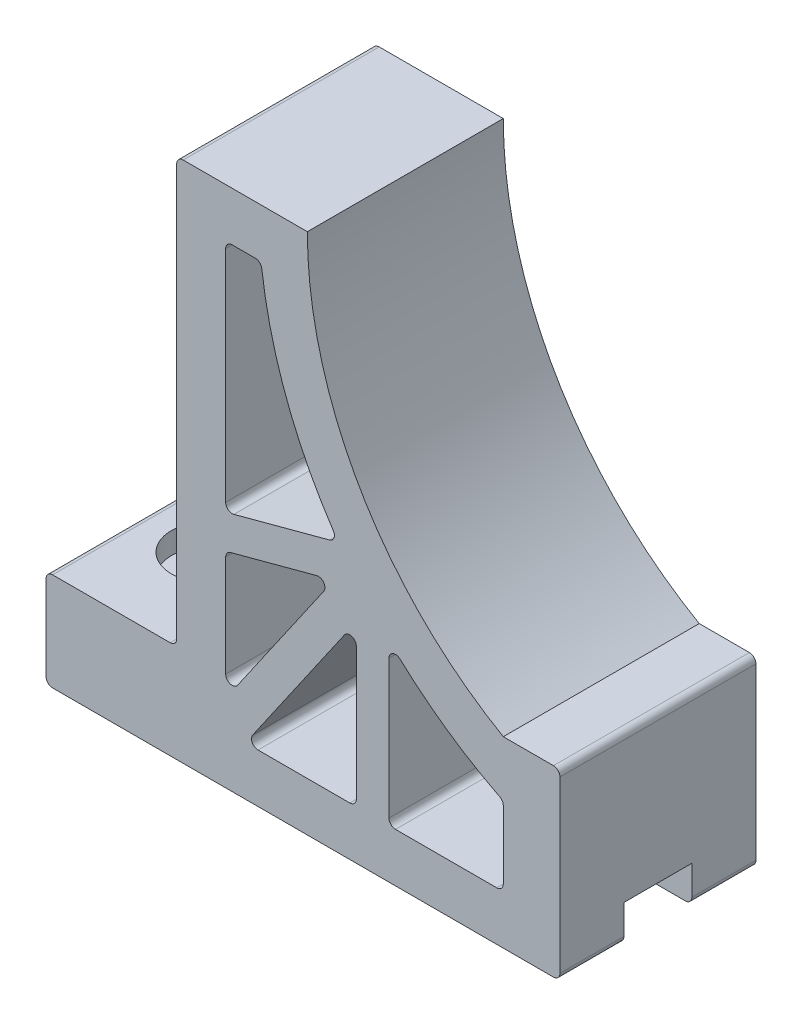
SolidWorks part; units mm, degrees
ref_plane "Front Plane" through (0, 0, 0) normal (0, 0, 1) x (1, 0, 0)
ref_plane "Top Plane" through (0, 0, 0) normal (0, 1, 0) x (1, 0, 0)
ref_plane "Right Plane" through (0, 0, 0) normal (1, 0, 0) x (0, 0, -1)
sketch "Sketch1" plane through (0, 0, 0) normal (0, 0, 1) x (1, 0, 0)
  line L1 (101.6, -50.8) -> (-101.6, -50.8)
  line L2 (101.6, -50.8) -> (101.6, 50.8)
  line L3 (101.6, 50.8) -> (-101.6, 50.8)
  line L4 (-101.6, -50.8) -> (-101.6, 50.8)
  line L5 (101.6, -50.8) -> (-101.6, 50.8) construction
  line L6 (101.6, 50.8) -> (-101.6, -50.8) construction
  point P0 (0, 0)
  dimension "D1" = 203.2
  dimension "4" = 101.6
extrude "Boss-Extrude1" add sketch "Sketch1" along normal blind 38.1
sketch "Sketch2" plane through (0, 0, 38.1) normal (0, 0, 1) x (1, 0, 0)
  line L0 (-101.6, -50.8) -> (101.6, -50.8) construction
  circle A0 centre (0, 50.8) radius 76.2
  dimension "D1" = 152.4
  dimension "D2" = 101.6
extrude "Cut-Extrude1" cut sketch "Sketch2" against normal through all
sketch "Sketch3" plane through (-101.6, 0, 0) normal (-1, 0, 0) x (0, 0, 1)
  line L0 (38.1, 50.8) -> (38.1, -50.8) construction
  line L1 (0, -50.8) -> (38.1, -50.8)
  line L2 (0, -50.8) -> (0, -31.75)
  line L3 (0, -31.75) -> (38.1, -31.75)
  line L4 (38.1, -50.8) -> (38.1, -31.75)
  dimension "D1" = 19.05
extrude "Boss-Extrude2" add sketch "Sketch3" along normal blind 25.4
sketch "Sketch4" plane through (0, 0, 38.1) normal (0, 0, 1) x (1, 0, 0)
  line L7 (-85.1942, 41.275) -> (-92.075, 41.275)
  line L8 (-92.075, 41.275) -> (-92.075, -41.275)
  line L9 (-92.075, -41.275) -> (-36.6025, -41.275)
  line L10 (-36.6025, -41.275) -> (-36.6025, -26.7179)
  line L11 (-101.6, 50.8) -> (-101.6, -31.75) construction
  line L12 (-76.2, 50.8) -> (-101.6, 50.8) construction
  line L13 (-127, -50.8) -> (101.6, -50.8) construction
  arc A4 (-36.6025, -26.7179) -> (-85.1942, 41.275) centre (0, 50.8) cw
  dimension "D1" = 85.725
  dimension "D2" = 9.525
  dimension "D3" = 9.525
  dimension "D4" = 9.525
extrude "Cut-Extrude2" cut sketch "Sketch4" against normal through all
sketch "Sketch5" plane through (0, 0, 38.1) normal (0, 0, 1) x (1, 0, 0)
  line L0 (-63.5, 0) -> (-97.8822, -9.2127) construction
  line L1 (-62.6782, -3.0668) -> (-97.0604, -12.2795)
  line L2 (-64.3218, 3.0668) -> (-98.7039, -6.1459)
  line L3 (0, 0) -> (-140.7402, 0) construction
  arc A0 (-62.6782, -3.0668) -> (-64.3218, 3.0668) centre (-63.5, 0) ccw
  arc A1 (-98.7039, -6.1459) -> (-97.0604, -12.2795) centre (-97.8822, -9.2127) ccw
  point P2 (-80.6911, -4.6063)
  dimension "D1" = 3.175
  dimension "D2" = 63.5
  dimension "D3" = 15
extrude "Boss-Extrude3" add sketch "Sketch5" against normal blind 38.1
sketch "Sketch6" plane through (0, 0, 38.1) normal (0, 0, 1) x (1, 0, 0)
  line L0 (-63.5, 0) -> (-92.075, -41.275) construction
  line L1 (-60.8895, -1.8072) -> (-89.4645, -43.0822)
  line L2 (-66.1105, 1.8072) -> (-94.6855, -39.4678)
  arc A0 (-60.8895, -1.8072) -> (-66.1105, 1.8072) centre (-63.5, 0) ccw
  arc A1 (-94.6855, -39.4678) -> (-89.4645, -43.0822) centre (-92.075, -41.275) ccw
  point P3 (-77.7875, -20.6375)
  dimension "D2" = 3.175
  dimension "D1" = 63.5
extrude "Boss-Extrude4" add sketch "Sketch6" against normal blind 38.1
sketch "Sketch7" plane through (0, 0, 38.1) normal (0, 0, 1) x (1, 0, 0)
  line L0 (-63.5, 0) -> (-63.5, -43.7075) construction
  line L1 (-60.325, 0) -> (-60.325, -43.7075)
  line L2 (-66.675, 0) -> (-66.675, -43.7075)
  arc A0 (-60.325, 0) -> (-66.675, 0) centre (-63.5, 0) ccw
  arc A1 (-66.675, -43.7075) -> (-60.325, -43.7075) centre (-63.5, -43.7075) ccw
  point P2 (-63.5, -21.8537)
  dimension "D2" = 3.175
  dimension "D1" = 63.5
extrude "Boss-Extrude5" add sketch "Sketch7" against normal blind 38.1
fillet "Fillet1" radius 1.27 11 edges at (-92.075, -4.3696, 19.05) (-92.075, -10.9437, 19.05) (-92.075, 41.275, 19.05) (-85.1942, 41.275, 19.05) (-127, -31.75, 19.05) (-101.6, -31.75, 19.05) (-101.6, 50.8, 19.05) (-36.6025, -26.7179, 19.05) (-70.1366, 1.5087, 19.05) (-66.675, -41.275, 19.05) (-60.325, -41.275, 19.05)
fillet "Fillet2" radius 1.27 5 edges at (-60.325, -10.1071, 19.05) (-88.2134, -41.275, 19.05) (-66.675, -10.164, 19.05) (-92.075, -35.6971, 19.05) (-71.035, -5.306, 19.05)
sketch "Sketch8" plane through (0, 0, 38.1) normal (0, 0, 1) x (1, 0, 0)
  line L0 (-127, -50.8) -> (101.6, -50.8) construction
  line L1 (150.7225, 101.6) -> (-27.0775, 101.6)
  line L2 (150.7225, 101.6) -> (150.7225, -50.8)
  line L3 (150.7225, -50.8) -> (-27.0775, -50.8)
  line L4 (-27.0775, 101.6) -> (-27.0775, -50.8)
  line L5 (-36.6025, -41.275) -> (-36.6025, -27.5186) construction
  dimension "D1" = 9.525
  dimension "D2" = 177.8
  dimension "D3" = 152.4
extrude "Cut-Extrude4" cut sketch "Sketch8" against normal through all
fillet "Fillet3" radius 1.27 4 edges at (-127, -50.8, 19.05) (-27.0775, -50.8, 19.05) (-27.0775, -20.4267, 19.05) (-36.6025, -41.275, 19.05)
hole_wizard "CBORE for 5/16 Button Head Cap Screw1" positions "Sketch9" profile "Sketch10" counterbore size "5/16" standard "ANSI Inch" end condition through all
sketch "Sketch9" plane through (0, -31.75, 0) normal (0, 1, 0) x (1, 0, 0)
  line L0 (-125.73, 0) -> (-102.87, 0) construction
  line L1 (-127, -38.1) -> (-127, 0) construction
  point P0 (-114.3, -19.05)
  dimension "D1" = 19.05
  dimension "D2" = 12.7
sketch "Sketch10" plane through (-114.3, -31.75, 19.05) normal (1, 0, 0) x (0, 0, 1)
  line L0 (0, 0) -> (0, 19.05)
  line L1 (0, 19.05) -> (4.2164, 19.05)
  line L3 (4.2164, 19.05) -> (4.2164, 4.2164)
  line L4 (4.2164, 4.2164) -> (7.3419, 4.2164)
  line L5 (7.3419, 4.2164) -> (7.3419, 0)
  line L7 (7.3419, 0) -> (0, 0)
  line L11 (0, -6.35) -> (0, 107.95) construction
  dimension "Thru Hole Dia." = 8.4328
  dimension "Thru Hole Depth" = 19.05
  dimension "C'Bore Dia." = 14.6837
  dimension "C'Bore Depth" = 4.2164
sketch "Sketch11" plane through (0, 0, 38.1) normal (0, 0, 1) x (1, 0, 0)
  line L0 (-125.73, -50.8) -> (-28.3475, -50.8) construction
  line L1 (-38.1, -50.8) -> (-27.0775, -50.8)
  line L2 (-38.1, -50.8) -> (-38.1, -15.1911)
  line L3 (-38.1, -15.1911) -> (-27.0775, -15.1911)
  line L4 (-27.0775, -50.8) -> (-27.0775, -15.1911)
  line L5 (-27.0775, -21.2973) -> (-27.0775, -49.53) construction
  dimension "D1" = 65.9911
  dimension "D2" = 76.2
extrude "Boss-Extrude6" add sketch "Sketch11" against normal blind 38.1
fillet "Fillet4" radius 1.27 2 edges at (-27.0775, -50.8, 19.05) (-27.0775, -15.1911, 19.05)
sketch "Sketch15" plane through (-27.0775, 0, 0) normal (1, 0, 0) x (0, 0, -1)
  line L0 (0, -50.8) -> (-38.1, -50.8) construction
  line L1 (-25.654, -43.815) -> (-12.446, -43.815)
  line L2 (-25.654, -43.815) -> (-25.654, -50.8)
  line L3 (-25.654, -50.8) -> (-12.446, -50.8)
  line L4 (-12.446, -43.815) -> (-12.446, -50.8)
  line L5 (-19.05, -50.8) -> (-19.05, -35.9664) construction
  dimension "D1" = 13.208
  dimension "D2" = 6.604
  dimension "D3" = 6.985
extrude "Cut-Extrude6" cut sketch "Sketch15" against normal blind 19.05
fillet "Fillet5" radius 1.27 2 edges at (-38.1, -25.993, 19.05) (-38.1, -41.275, 19.05)
sketch "Sketch16" plane through (0, 0, 0) normal (0, 0, -1) x (-1, 0, 0)
  line L1 (0, -56.2472) -> (132.6709, -56.2472)
  line L2 (0, -56.2472) -> (0, 54.2603)
  line L3 (0, 54.2603) -> (132.6709, 54.2603)
  line L4 (132.6709, -56.2472) -> (132.6709, 54.2603)
extrude "Cut-Extrude8" [suppressed] cut sketch "Sketch16" against normal blind 34.925
equation "\"D2@Sketch15\"=\"D1@Sketch15\"/2"
